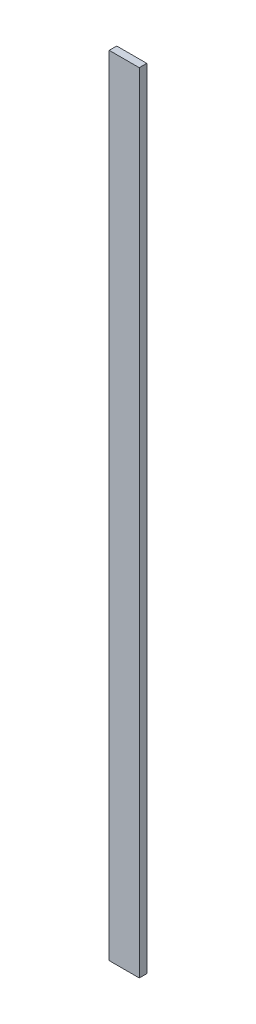
SolidWorks part; units mm, degrees
material "Balsa"
ref_plane "Front Plane" through (0, 0, 0) normal (1, 0, 0) x (0, 1, 0)
ref_plane "Top Plane" through (0, 0, 0) normal (0, 0, 1) x (0, 1, 0)
ref_plane "Right Plane" through (0, 0, 0) normal (0, 1, 0) x (-1, 0, 0)
sketch "Sketch1" plane through (0, 0, 0) normal (0, 0, 1) x (0, 1, 0)
  line L1 (-157.5, -6) -> (157.5, -6)
  line L2 (-157.5, -6) -> (-157.5, 6)
  line L3 (-157.5, 6) -> (157.5, 6)
  line L4 (157.5, -6) -> (157.5, 6)
  line L5 (-157.5, -6) -> (157.5, 6) construction
  line L6 (-157.5, 6) -> (157.5, -6) construction
  point P0 (0, 0)
  dimension "D1" = 315
  dimension "D2" = 12
extrude "Boss-Extrude1" add sketch "Sketch1" along normal blind 3
